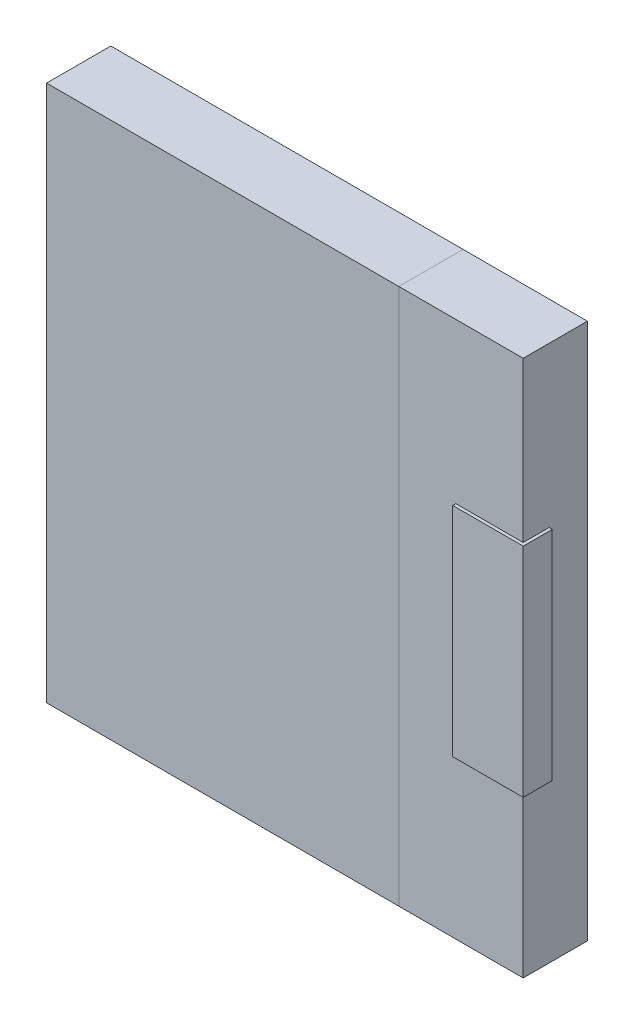
SolidWorks part; units mm, degrees
ref_plane "Front Plane" through (0, 0, 0) normal (0, 0, 1) x (1, 0, 0)
ref_plane "Top Plane" through (0, 0, 0) normal (0, 1, 0) x (1, 0, 0)
ref_plane "Right Plane" through (0, 0, 0) normal (1, 0, 0) x (0, 0, -1)
sketch "Sketch1" plane through (0, 0, 0) normal (0, 0, 1) x (1, 0, 0)
  line L1 (-230, 259) -> (230, 259)
  line L2 (-230, 259) -> (-230, -259)
  line L3 (-230, -259) -> (230, -259)
  line L4 (230, 259) -> (230, -259)
  line L5 (-230, 259) -> (230, -259) construction
  line L6 (-230, -259) -> (230, 259) construction
  point P0 (0, 0)
  dimension "D1" = 518
  dimension "D2" = 460
extrude "Boss-Extrude1" add sketch "Sketch1" along normal mid plane 62 contours L1 L4 L3 L2
sketch "Sketch2" plane through (0, 0, 31) normal (0, 0, 1) x (1, 0, 0)
  line L0 (110, -259) -> (110, 259)
  line L1 (-230, -259) -> (230, -259) construction
  line L2 (-230, 259) -> (230, 259) construction
  line L3 (230, 259) -> (230, -259) construction
  dimension "D1" = 120
split "Split1" trim tools "Sketch2" bodies to split 101 resulting bodies 102 103
sketch "Sketch3" plane through (0, 0, 31) normal (0, 0, 1) x (1, 0, 0)
  line L0 (110, 259) -> (230, 259) construction
  line L1 (165, 105) -> (233, 105)
  line L2 (165, 105) -> (165, -105)
  line L3 (165, -105) -> (233, -105)
  line L4 (233, 105) -> (233, -105)
  line L5 (165, 105) -> (233, -105) construction
  line L6 (165, -105) -> (233, 105) construction
  line L7 (110, -259) -> (230, -259) construction
  line L8 (230, 259) -> (230, -259) construction
  point P0 (199, 0)
  dimension "D1" = 154
  dimension "D2" = 154
  dimension "D3" = 68
  dimension "D4" = 3
extrude "Boss-Extrude2" add sketch "Sketch3" along normal blind 3 separate body
sketch "Sketch4" plane through (0, 0, 31) normal (0, 0, -1) x (-1, 0, 0)
  line L0 (-230, 259) -> (-230, -259) construction
  line L1 (-230, 105) -> (-230, -105)
  line L4 (-233, 105) -> (-233, -105)
  line L5 (-233, -105) -> (-165, -105)
  line L6 (-165, -105) -> (-165, 105)
  line L7 (-165, 105) -> (-233, 105)
  line L8 (-233, 105) -> (-233, -105)
  line L9 (-233, -105) -> (-230, -105)
  line L11 (-230, 105) -> (-233, 105)
  dimension "D1" = 0
extrude "Boss-Extrude3" add sketch "Sketch4" along normal blind 25 separate body
combine bodies "Combine1" operation type add bodies to combine 104 105
shell "Shell1" thickness 1
shell "Shell2" thickness 1
sketch "Sketch6" plane through (-230, 0, 0) normal (-1, 0, 0) x (0, 0, 1)
  line L0 (-31, 259) -> (-31, -259) construction
  line L1 (31, -259) -> (-31, -259) construction
  line L2 (31, 259) -> (-31, 259) construction
  circle A0 centre (-16, 201.25) radius 3.25
  circle A1 centre (-16, 181.25) radius 3.25
  circle A2 centre (-16, 161.25) radius 3.25
  circle A3 centre (-16, -162.25) radius 3.25
  circle A4 centre (-16, -182.25) radius 3.25
  circle A5 centre (-16, -202.25) radius 3.25
  dimension "D1" = 6.5
  dimension "D2" = 20
  dimension "D3" = 20
  dimension "D4" = 20
  dimension "D5" = 20
  dimension "D6" = 15
  dimension "D7" = 56.75
  dimension "D8" = 57.75
extrude "Cut-Extrude2" cut sketch "Sketch6" against normal blind 5
